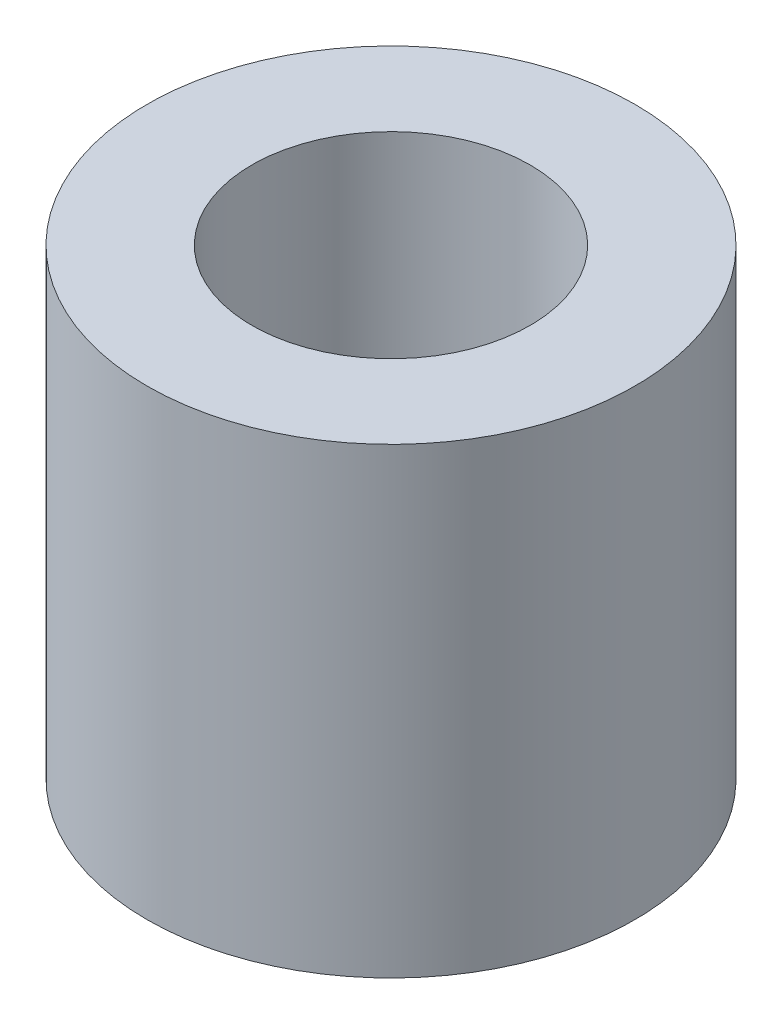
SolidWorks part; units mm, degrees
material "Copper"
ref_plane "Front Plane" through (0, 0, 0) normal (0, 0, 1) x (1, 0, 0)
ref_plane "Top Plane" through (0, 0, 0) normal (0, 1, 0) x (1, 0, 0)
ref_plane "Right Plane" through (0, 0, 0) normal (1, 0, 0) x (0, 0, -1)
sketch "Sketch1" plane through (0, 0, 0) normal (0, 1, 0) x (1, 0, 0)
  circle A0 centre (0, 0) radius 12.4
  circle A1 centre (0, 0) radius 21.75
  dimension "D1" = 43.5
  dimension "D2" = 24.8
extrude "Boss-Extrude1" add sketch "Sketch1" along normal mid plane 41.2
